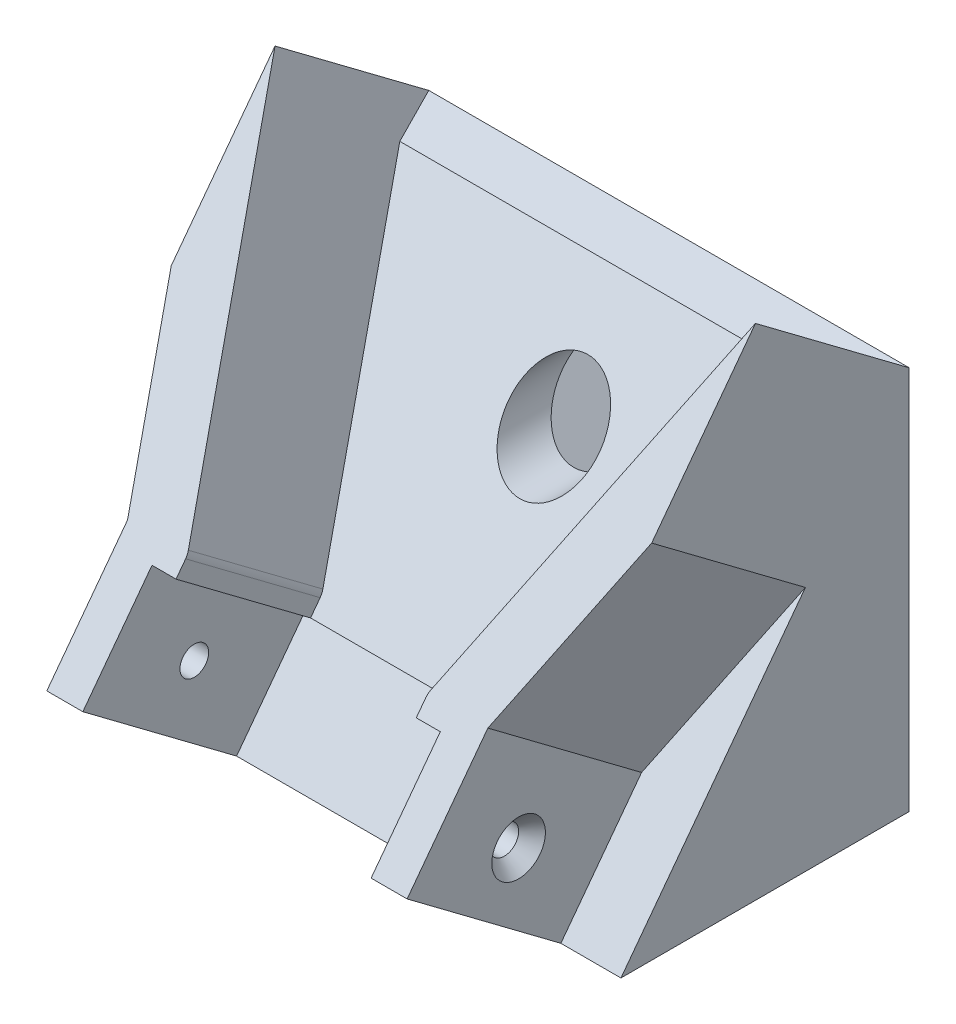
SolidWorks part; units mm, degrees
ref_plane "Front Plane" through (0, 0, 0) normal (0, 0, 1) x (1, 0, 0)
ref_plane "Top Plane" through (0, 0, 0) normal (0, 1, 0) x (1, 0, 0)
ref_plane "Right Plane" through (0, 0, 0) normal (1, 0, 0) x (0, 0, -1)
sketch "Sketch4" plane through (0, 0, 0) normal (1, 0, 0) x (0, 0, -1)
  line L0 (0, 50.8) -> (-38.1001, 0)
  line L1 (-38.1001, 0) -> (0, 0)
  line L2 (0, 0) -> (0, 50.8)
  dimension "D1" = 53.13
  dimension "D2" = 50.8
extrude "Boss-Extrude2" add sketch "Sketch4" along normal blind 63.5 contours L0 L1 L2
shell "Shell1" thickness 2.54
sketch "Sketch5" plane through (0, 18.2881, 24.384) normal (0, 0.6, 0.8) x (1, 0, 0)
  line L0 (12.7, -22.8601) -> (12.7, -7.6201)
  line L1 (63.5, -22.8601) -> (0, -22.8601) construction
  line L2 (15.875, -5.0801) -> (0, 40.6399)
  line L3 (0, 40.6399) -> (0, 17.7799)
  line L4 (0, 40.6399) -> (0, -22.8601) construction
  line L5 (0, 17.7799) -> (7.9375, -5.0801)
  line L6 (7.9375, -5.0801) -> (7.9375, -22.8601)
  line L7 (7.9375, -22.8601) -> (12.7, -22.8601)
  line L8 (55.5625, -5.0801) -> (55.5625, -22.8601)
  line L9 (55.5625, -22.8601) -> (50.8, -22.8601)
  line L14 (50.8, -22.8601) -> (50.8, -7.6201)
  line L17 (63.5, 40.6399) -> (63.5, -22.8601) construction
  line L19 (15.875, -5.0801) -> (15.875, -7.6201)
  line L20 (15.875, -7.6201) -> (12.7, -7.6201)
  line L21 (50.8, -7.6201) -> (47.625, -7.6201)
  line L22 (47.625, -7.6201) -> (47.625, -5.0801)
  line L24 (47.625, -5.0801) -> (63.5, 40.6399)
  line L25 (63.5, 40.6399) -> (63.5, 17.7799)
  line L26 (63.5, 17.7799) -> (55.5625, -5.0801)
  dimension "D1" = 38.1
  dimension "D2" = 4.7625
  dimension "D3" = 3.175
  dimension "D4" = 4.7625
  dimension "D5" = 7.9375
  dimension "D6" = 2.54
  dimension "D7" = 3.175
  dimension "D8" = 17.78
  dimension "D10" = 17.78
  dimension "D12" = 2.54
extrude "Boss-Extrude4" add sketch "Sketch5" along normal blind 25.4
fillet "Fillet1" radius 2.54 2 edges at (15.875, 21.844, 37.5921) (47.625, 21.844, 37.5921)
sketch "Sketch6" plane through (7.9375, 0, 0) normal (-1, 0, 0) x (0, 0, 1)
  line L0 (58.4201, 15.24) -> (38.1001, 0) construction
  line L1 (47.7521, 29.464) -> (58.4201, 15.24) construction
  point P0 (43.6881, 13.716)
  dimension "D1" = 7.62
  dimension "D2" = 12.7
hole_wizard "CSK for #6 Flat Head Machine Screw2" positions "Sketch6" profile "Sketch7" countersink size "#6" standard "ANSI Inch"
sketch "Sketch7" plane through (7.9375, 13.716, 43.6881) normal (0, 1, 0) x (0, 0, 1)
  line L0 (0, 0) -> (0, 4.7625)
  line L1 (0, 4.7625) -> (1.8986, 4.7625)
  line L2 (1.8986, 4.7625) -> (1.8986, 1.892)
  line L3 (1.8986, 1.892) -> (3.5433, 0)
  line L5 (3.5433, 0) -> (0, 0)
  line L6 (-1.8986, 1.892) -> (-3.5433, 0) construction
  line L11 (0, -6.35) -> (0, 107.95) construction
  dimension "Thru Hole Dia." = 3.7973
  dimension "Thru Hole Depth" = 4.7625
  dimension "Near C'Sink Dia." = 7.0866
  dimension "Near C'Sink Angle" = 82
sketch "Sketch8" plane through (55.5625, 0, 0) normal (1, 0, 0) x (0, 0, -1)
  line L0 (-58.4201, 15.24) -> (-38.1001, 0) construction
  line L1 (-58.4201, 15.24) -> (-47.7521, 29.464) construction
  point P0 (-43.6881, 13.716)
  dimension "D1" = 7.62
  dimension "D2" = 12.7
hole_wizard "CSK for #6 Flat Head Machine Screw1" positions "Sketch8" profile "Sketch9" countersink size "#6" standard "ANSI Inch" end condition up to next
sketch "Sketch9" plane through (55.5625, 13.716, 43.6881) normal (0, 1, 0) x (0, 0, -1)
  line L0 (0, 0) -> (0, 4.7625)
  line L1 (0, 4.7625) -> (1.8986, 4.7625)
  line L2 (1.8986, 4.7625) -> (1.8986, 1.892)
  line L3 (1.8986, 1.892) -> (3.5433, 0)
  line L5 (3.5433, 0) -> (0, 0)
  line L6 (-1.8986, 1.892) -> (-3.5433, 0) construction
  line L11 (0, -6.35) -> (0, 107.95) construction
  dimension "Thru Hole Dia." = 3.7973
  dimension "Thru Hole Depth" = 4.7625
  dimension "Near C'Sink Dia." = 7.0866
  dimension "Near C'Sink Angle" = 82
sketch "Sketch10" plane through (0, 0, 0) normal (0, 0, -1) x (-1, 0, 0)
  line L1 (0, 0) -> (0, 50.8) construction
  line L2 (-63.5, 50.8) -> (0, 50.8) construction
  circle A0 centre (-31.75, 35.8) radius 3.5
  dimension "D2" = 7
  dimension "D1" = 15
  dimension "D3" = 31.75
extrude "Cut-Extrude1" cut sketch "Sketch10" against normal up to next
sketch "Sketch11" plane through (0, 18.2881, 24.384) normal (0, 0.6, 0.8) x (1, 0, 0)
  line L0 (1.7639, 35.5599) -> (61.7361, 35.5599)
  line L1 (61.7361, 35.5599) -> (47.7655, -4.6754)
  line L2 (1.7639, 35.5599) -> (15.7345, -4.6754)
  line L3 (15.875, -7.6201) -> (47.625, -7.6201)
  line L4 (15.875, -5.5086) -> (15.875, -7.6201)
  line L5 (47.625, -5.5086) -> (47.625, -7.6201)
  line L6 (63.5, 40.6399) -> (0, 40.6399) construction
  arc A0 (15.7345, -4.6754) -> (15.875, -5.5086) centre (13.335, -5.5086) cw
  arc A1 (47.7655, -4.6754) -> (47.625, -5.5086) centre (50.165, -5.5086) ccw
  dimension "D1" = 5.08
extrude "Boss-Extrude6" add sketch "Sketch11" along normal blind 3.175 contours L0 L1 A1 L5 L3 L4 A0 L2
sketch "Sketch12" plane through (44.0751, -12.243, 9.1823) normal (-0.9447, 0.2624, -0.1968) x (-0.1631, 0.1447, 0.9759)
  line L0 (2.4205, 63.4495) -> (-3.0084, 66.5358)
  line L1 (-3.0084, 66.5358) -> (-0.3341, 61.8705)
  line L2 (-0.3341, 61.8705) -> (2.4205, 63.4495)
sketch "Sketch14" plane through (12.5928, 3.498, -2.6235) normal (0.9447, 0.2624, -0.1968) x (-0.1678, -0.129, -0.9773)
  line L0 (-6.5528, 48.5799) -> (-12.0317, 45.5832)
  line L1 (-12.0317, 45.5832) -> (-9.3035, 43.9591)
  line L2 (-9.3035, 43.9591) -> (-6.5528, 48.5799)
loft "Loft2" add profiles "Sketch14", "Sketch12"
sketch "Sketch15" plane through (0, 0, 2.54) normal (0, 0, 1) x (1, 0, 0)
  circle A0 centre (31.75, 35.8) radius 6
  dimension "D1" = 12
extrude "Cut-Extrude2" cut sketch "Sketch15" along normal blind 38.735
